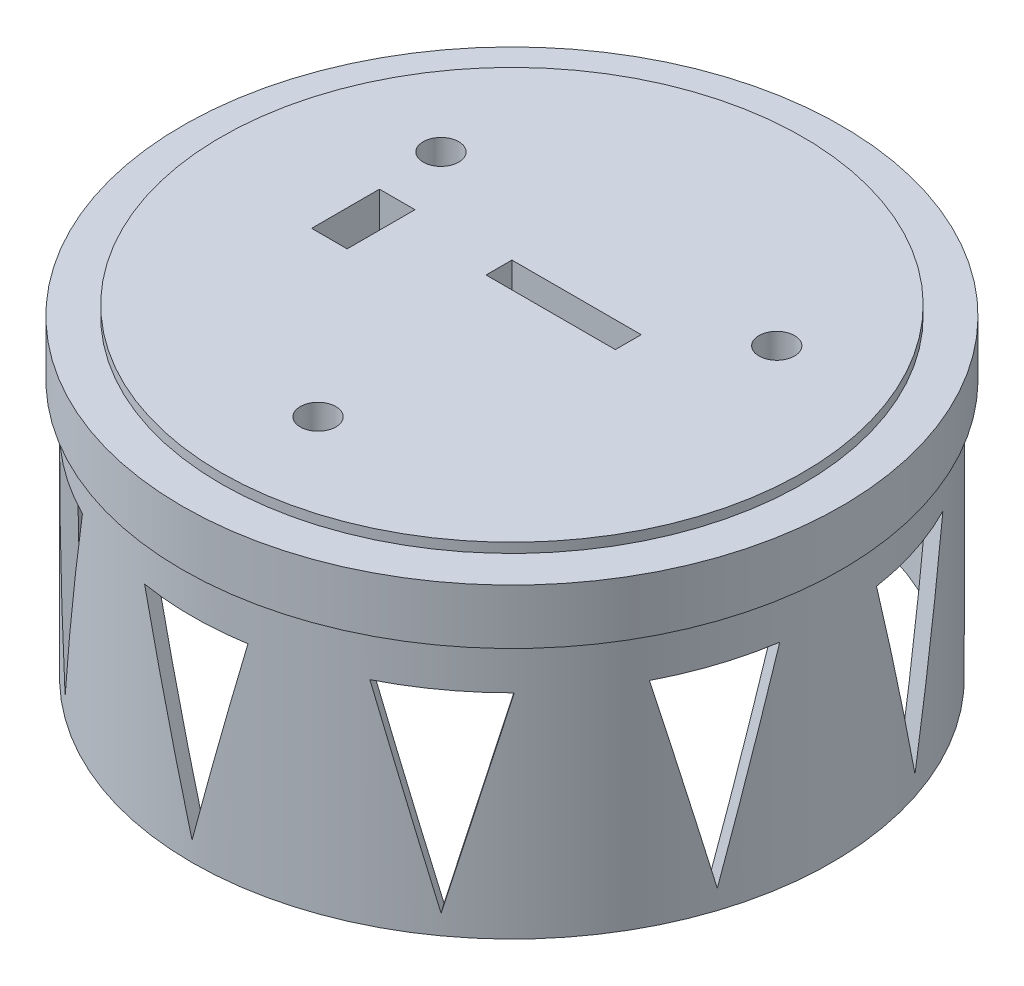
SolidWorks part; units mm, degrees
material "ABS"
ref_plane "Спереди" through (0, 0, 0) normal (0, 0, 1) x (1, 0, 0)
ref_plane "Сверху" through (0, 0, 0) normal (0, 1, 0) x (1, 0, 0)
ref_plane "Справа" through (0, 0, 0) normal (1, 0, 0) x (0, 0, -1)
sketch "Эскиз2" plane through (0, 0, 0) normal (0, 0, 1) x (1, 0, 0)
  line L0 (0, 0) -> (0, 74.988) construction
  line L1 (0, 0) -> (-49.5, 0)
  line L2 (-49.5, 0) -> (-49.5, -40)
  line L3 (-49.5, -40) -> (-47.5, -40)
  line L4 (-47.5, -40) -> (-47.5, -5.5)
  line L5 (-44.5, -2.5) -> (0, -2.5)
  line L6 (0, -2.5) -> (0, 0)
  arc A0 (-47.5, -5.5) -> (-44.5, -2.5) centre (-44.5, -5.5) cw
  dimension "D5" = 3
  dimension "D1" = 49.5
  dimension "D2" = 40
  dimension "D3" = 2
  dimension "D4" = 2.5
revolve "Основа" add sketch "Эскиз2" angle 360 about L0
sketch "Эскиз4" plane through (0, 0, 0) normal (0, 0, 1) x (1, 0, 0)
  line L0 (0, 0) -> (0, -22) construction
  line L1 (-8, -37) -> (8, -37) construction
  line L2 (-8, -37) -> (-8, -7) construction
  line L3 (-8, -7) -> (8, -7)
  line L4 (8, -37) -> (8, -7) construction
  line L5 (-8, -37) -> (8, -7) construction
  line L6 (-8, -7) -> (8, -37) construction
  line L8 (-8, -7) -> (0, -37)
  line L9 (0, -37) -> (8, -7)
  point P0 (0, -22)
  dimension "D1" = 30
  dimension "D2" = 16
  dimension "D3" = 7
  dimension "D4" = 29.863
  dimension "D6" = 75.069
extrude "Вырез облегчение" cut sketch "Эскиз4" against normal mid plane 141.7
pattern_circular "Массив вырезов" count 5 over 360 about axis through (0, 0, 0) along (0, 1, 0) of "Вырез облегчение"
sketch "Эскиз7" plane through (0, 0, 0) normal (0, 1, 0) x (1, 0, 0)
  circle A0 centre (0, 0) radius 51
  dimension "D1" = 102
extrude "Бобышка-Вытянуть1" add sketch "Эскиз7" along normal blind 10
sketch "Эскиз8" plane through (0, 10, 0) normal (0, 1, 0) x (1, 0, 0)
  circle A0 centre (0, 0) radius 45
  circle A1 centre (0, 0) radius 51 construction
  circle A2 centre (0, 0) radius 51
  dimension "D1" = 90
extrude "Вырез-Вытянуть1" cut sketch "Эскиз8" against normal blind 1.5
sketch "Эскиз9" plane through (0, 10, 0) normal (0, 1, 0) x (1, 0, 0)
  circle A0 centre (0, 0) radius 6
  dimension "D1" = 12
extrude "Вырез-Вытянуть2" [suppressed] cut sketch "Эскиз9" against normal through all
sketch "Эскиз10" plane through (0, 10, 0) normal (0, 1, 0) x (1, 0, 0)
  circle A0 centre (0, 30) radius 4.5
  circle A1 centre (0, -30) radius 2.75
  circle A2 centre (25.9808, -15) radius 4.5
  circle A3 centre (-25.9808, 15) radius 2.75
  circle A4 centre (-25.9808, -15) radius 4.5
  circle A5 centre (25.9808, 15) radius 2.75
  point P15 (0, 0)
  dimension "D1" = 9
  dimension "D3" = 5.5
  dimension "D2" = 30
  dimension "D4" = 30
  dimension "D5" = 3
extrude "Вырез-Вытянуть5" cut sketch "Эскиз10" against normal blind 8 contours A3 | A5 | A1
chamfer "Фаска2" [suppressed] distance 0.5 angle 45
sketch "Эскиз11" plane through (0, 10, 0) normal (0, 1, 0) x (1, 0, 0)
  line L1 (-6, 2) -> (-6, 6)
  line L2 (-6, 2) -> (14, 2)
  line L3 (14, 2) -> (14, 6)
  line L4 (-6, 6) -> (14, 6)
  line L5 (-6, 2) -> (14, 6) construction
  line L6 (14, 2) -> (-6, 6) construction
  line L7 (-20.25, 5.25) -> (-20.25, -5.25)
  line L8 (-20.25, 5.25) -> (-25.75, 5.25)
  line L9 (-25.75, 5.25) -> (-25.75, -5.25)
  line L10 (-20.25, -5.25) -> (-25.75, -5.25)
  line L11 (-20.25, 5.25) -> (-25.75, -5.25) construction
  line L12 (-25.75, 5.25) -> (-20.25, -5.25) construction
  point P4 (4, 4)
  point P11 (-23, 0)
  dimension "D1" = 4
  dimension "D2" = 20
  dimension "D3" = 4
  dimension "D4" = 23
  dimension "D5" = 5.5
  dimension "D6" = 10.5
  dimension "D7" = 4
extrude "Вырез-Вытянуть6" cut sketch "Эскиз11" against normal up to next
